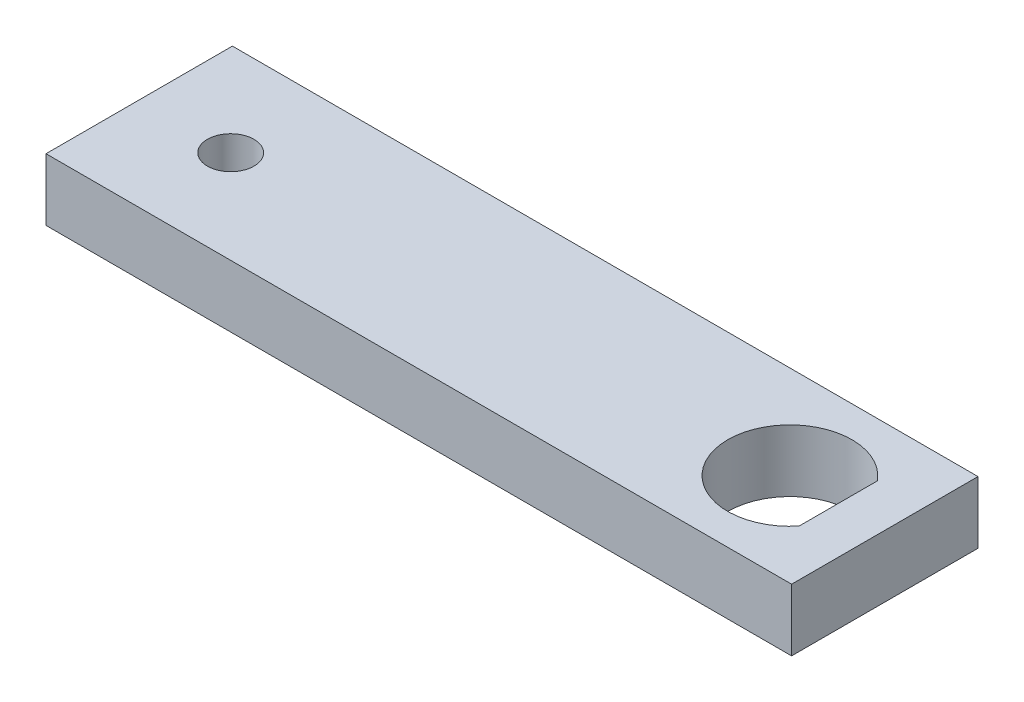
SolidWorks part; units mm, degrees
ref_plane "Front Plane" through (0, 0, 0) normal (0, 0, 1) x (1, 0, 0)
ref_plane "Top Plane" through (0, 0, 0) normal (0, 1, 0) x (1, 0, 0)
ref_plane "Right Plane" through (0, 0, 0) normal (1, 0, 0) x (0, 0, -1)
sketch "Sketch1" plane through (0, 0, 0) normal (0, 1, 0) x (1, 0, 0)
  line L0 (33.34, 3.9898) -> (33.34, -3.9898)
  line L1 (38.1, -9.525) -> (-38.1, -9.525)
  line L2 (38.1, -9.525) -> (38.1, 9.525)
  line L3 (38.1, 9.525) -> (-38.1, 9.525)
  line L4 (-38.1, -9.525) -> (-38.1, 9.525)
  line L5 (38.1, -9.525) -> (-38.1, 9.525) construction
  line L6 (38.1, 9.525) -> (-38.1, -9.525) construction
  circle A0 centre (-28.75, 0) radius 2.38
  arc A1 (33.34, 3.9898) -> (33.34, -3.9898) centre (28.4, 0) ccw
  point P0 (0, 0)
  dimension "D3" = 4.76
  dimension "D5" = 12.7
  dimension "D1" = 19.05
  dimension "D2" = 76.2
  dimension "D4" = 9.35
  dimension "D6" = 9.7
  dimension "D7" = 4.76
extrude "Boss-Extrude1" add sketch "Sketch1" along normal blind 6.35
